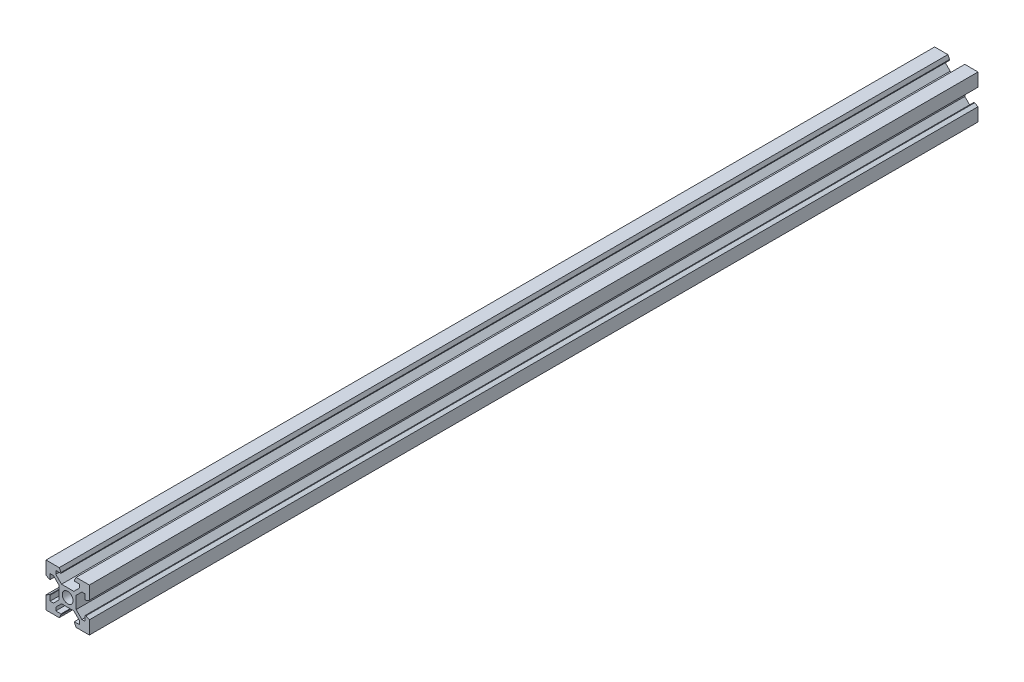
SolidWorks part; units mm, degrees
ref_plane "Front Plane" through (0, 0, 0) normal (0, 0, 1) x (1, 0, 0)
ref_plane "Top Plane" through (0, 0, 0) normal (0, 1, 0) x (1, 0, 0)
ref_plane "Right Plane" through (0, 0, 0) normal (1, 0, 0) x (0, 0, -1)
sketch "Sketch1" plane through (0, 0, 0) normal (0, 0, 1) x (1, 0, 0)
  line L0 (0, 20) -> (0, 13.8958)
  line L1 (0, 0) -> (20, 0)
  line L2 (0, 0) -> (0, 20)
  line L3 (0, 20) -> (20, 20)
  line L4 (20, 0) -> (20, 20)
  line L5 (0, 13.8958) -> (1.56, 13.1)
  line L6 (1.56, 13.1) -> (1.9, 13.1)
  line L7 (1.9, 13.1) -> (1.9, 15.5)
  line L8 (1.9, 15.5) -> (3.4393, 15.5)
  line L9 (3.4393, 15.5) -> (6.2656, 12.6737)
  line L10 (6.2656, 12.6737) -> (7.3263, 13.7344)
  line L11 (7.3263, 13.7344) -> (4.5, 16.5607)
  line L12 (4.5, 16.5607) -> (4.5, 18.1)
  line L13 (4.5, 18.1) -> (6.9, 18.1)
  line L14 (6.9, 18.1) -> (6.9, 18.44)
  line L15 (6.9, 18.44) -> (6.1, 20)
  line L16 (6.1, 20) -> (0, 20)
  line L17 (10, 10) -> (6.1, 13.9)
  line L18 (6.1, 6.1) -> (13.9, 6.1)
  line L19 (6.1, 6.1) -> (6.1, 13.9)
  line L20 (6.1, 13.9) -> (13.9, 13.9)
  line L21 (13.9, 6.1) -> (13.9, 13.9)
  line L22 (6.796, 13.204) -> (4.0494, 15.9506)
  line L23 (10, 10) -> (10, 24.9145) construction
  line L24 (13.1, 18.44) -> (13.9, 20)
  line L25 (13.1, 18.1) -> (13.1, 18.44)
  line L26 (15.5, 18.1) -> (13.1, 18.1)
  line L27 (15.5, 16.5607) -> (15.5, 18.1)
  line L28 (12.6737, 13.7344) -> (15.5, 16.5607)
  line L29 (13.7344, 12.6737) -> (12.6737, 13.7344)
  line L30 (16.5607, 15.5) -> (13.7344, 12.6737)
  line L31 (18.1, 15.5) -> (16.5607, 15.5)
  line L32 (18.1, 13.1) -> (18.1, 15.5)
  line L33 (18.44, 13.1) -> (18.1, 13.1)
  line L34 (20, 13.8958) -> (18.44, 13.1)
  line L35 (10, 10) -> (22.1718, 10)
  line L36 (20, 6.1042) -> (18.44, 6.9)
  line L37 (18.44, 6.9) -> (18.1, 6.9)
  line L38 (18.1, 6.9) -> (18.1, 4.5)
  line L39 (18.1, 4.5) -> (16.5607, 4.5)
  line L40 (16.5607, 4.5) -> (13.7344, 7.3263)
  line L41 (13.7344, 7.3263) -> (12.6737, 6.2656)
  line L42 (12.6737, 6.2656) -> (15.5, 3.4393)
  line L43 (15.5, 3.4393) -> (15.5, 1.9)
  line L44 (15.5, 1.9) -> (13.1, 1.9)
  line L45 (13.1, 1.9) -> (13.1, 1.56)
  line L46 (13.1, 1.56) -> (13.9, 0)
  line L47 (6.9, 1.56) -> (6.1, 0)
  line L48 (6.9, 1.9) -> (6.9, 1.56)
  line L49 (4.5, 1.9) -> (6.9, 1.9)
  line L50 (4.5, 3.4393) -> (4.5, 1.9)
  line L51 (7.3263, 6.2656) -> (4.5, 3.4393)
  line L52 (6.2656, 7.3263) -> (7.3263, 6.2656)
  line L53 (3.4393, 4.5) -> (6.2656, 7.3263)
  line L54 (1.9, 4.5) -> (3.4393, 4.5)
  line L55 (1.9, 6.9) -> (1.9, 4.5)
  line L56 (1.56, 6.9) -> (1.9, 6.9)
  line L57 (0, 6.1042) -> (1.56, 6.9)
  circle A0 centre (10, 10) radius 2.5
  point P21 (2.6697, 15.5)
  dimension "D3" = 5
  dimension "D1" = 20
  dimension "D2" = 20
  dimension "D4" = 10
  dimension "D5" = 10
  dimension "D6" = 7.8
  dimension "D7" = 7.8
  dimension "D8" = 6.1
  dimension "D9" = 6.1
  dimension "D10" = 6.9
  dimension "D11" = 6.9
  dimension "D12" = 6.1042
  dimension "D13" = 6.1
  dimension "D14" = 0.34
  dimension "D15" = 0.34
  dimension "D16" = 1.9
  dimension "D17" = 4.5
  dimension "D18" = 4.5
  dimension "D19" = 1.5
  dimension "D20" = 1.9
extrude "Boss-Extrude1" add sketch "Sketch1" along normal blind 410
